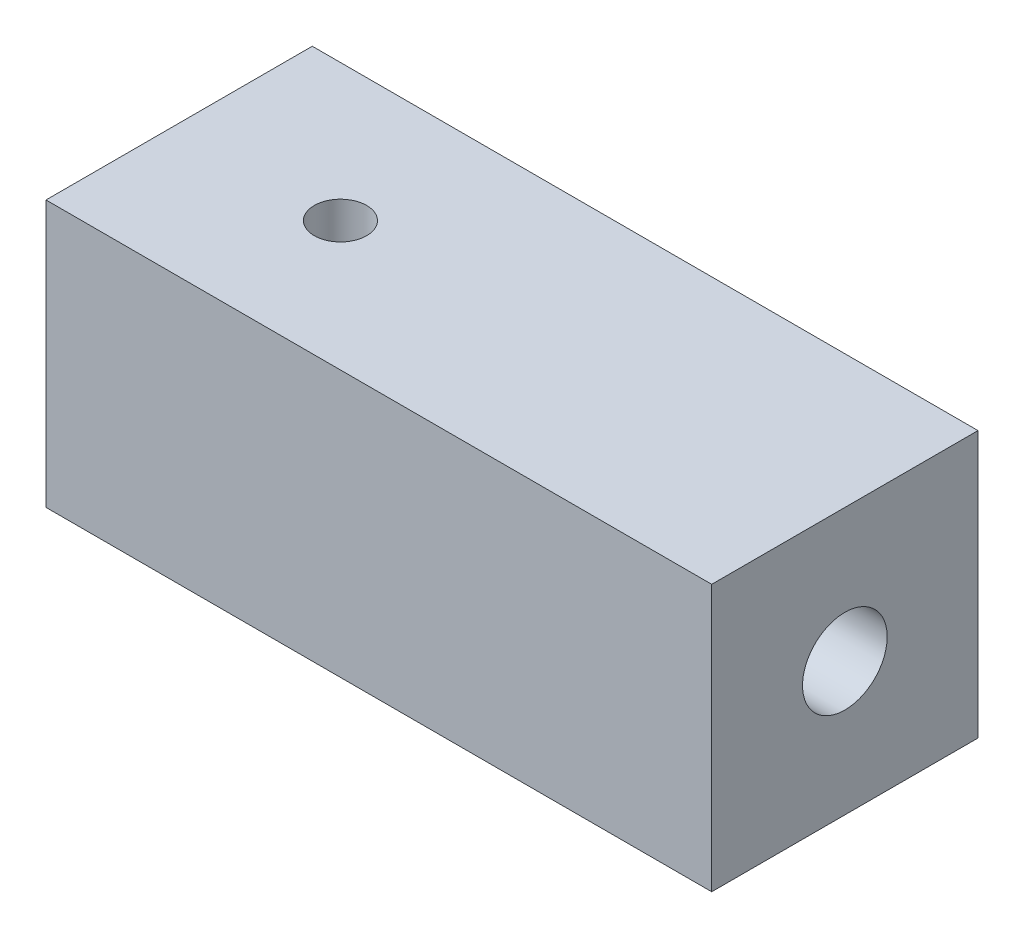
SolidWorks part; units mm, degrees
ref_plane "Front Plane" through (0, 0, 0) normal (0, 0, 1) x (1, 0, 0)
ref_plane "Top Plane" through (0, 0, 0) normal (0, 1, 0) x (1, 0, 0)
ref_plane "Right Plane" through (0, 0, 0) normal (1, 0, 0) x (0, 0, -1)
sketch "Sketch1" plane through (0, 0, 0) normal (1, 0, 0) x (0, 0, -1)
  line L1 (0, 0) -> (12.7, 0)
  line L2 (0, 0) -> (0, 12.7)
  line L3 (0, 12.7) -> (12.7, 12.7)
  line L4 (12.7, 0) -> (12.7, 12.7)
  dimension "D1" = 12.7
  dimension "D2" = 12.7
extrude "Boss-Extrude1" add sketch "Sketch1" along normal blind 31.75
hole_wizard "#10-32 Tapped Hole1" positions "Sketch3" profile "Sketch2" tap size "#10-32" standard "ANSI Inch"
sketch "Sketch3" plane through (31.75, 0.2399, -27.5152) normal (-1, 0, 0) x (0, 0, 1)
  line L0 (27.5152, 12.4601) -> (27.5152, -0.2399) construction
  line L1 (14.8152, -0.2399) -> (27.5152, 12.4601) construction
  line L3 (14.8152, 12.4601) -> (27.5152, -0.2399) construction
  point P0 (21.1652, 6.1101)
  point P9 (27.5152, 6.1101)
  dimension "D3" = 0
sketch "Sketch2" plane through (31.75, 6.35, -6.35) normal (0, 1, 0) x (0, 0, -1)
  line L0 (0, 0) -> (0, 13.1513)
  line L1 (0, 13.1513) -> (2.0193, 11.938)
  line L2 (2.0193, 11.938) -> (2.0193, 0)
  line L5 (2.0193, 0) -> (0, 0)
  line L10 (0, 13.1513) -> (-2.0193, 11.938) construction
  line L11 (0, -6.35) -> (0, 107.95) construction
  dimension "Tap Drill Dia." = 4.0386
  dimension "Tap Drill Depth" = 11.938
  dimension "Drill Angle" = 118
hole_wizard "M3x0.5 Tapped Hole1" positions "Sketch5" profile "Sketch4" tap size "M3x0.5" standard "ANSI Metric" end condition up to next
sketch "Sketch5" plane through (0.3974, 0, -0.6748) normal (0, 1, 0) x (1, 0, 0)
  line L2 (-0.3974, 5.4955) -> (11.2096, 5.4955) construction
  line L3 (-0.3974, 12.0252) -> (-0.3974, -0.6748) construction
  line L5 (31.3526, 12.0252) -> (31.3526, -0.6748) construction
  point P0 (7.4766, 5.4955)
  dimension "D1" = 23.876
sketch "Sketch4" plane through (7.874, 0, -6.1703) normal (1, 0, 0) x (0, 0, -1)
  line L0 (0, 0) -> (0, 12.7)
  line L1 (0, 12.7) -> (1.25, 12.7)
  line L2 (1.25, 12.7) -> (1.25, 0)
  line L5 (1.25, 0) -> (0, 0)
  line L11 (0, -6.35) -> (0, 107.95) construction
  dimension "Thread Major Dia." = 2.5
  dimension "Thru Tap Drill Depth" = 12.7
